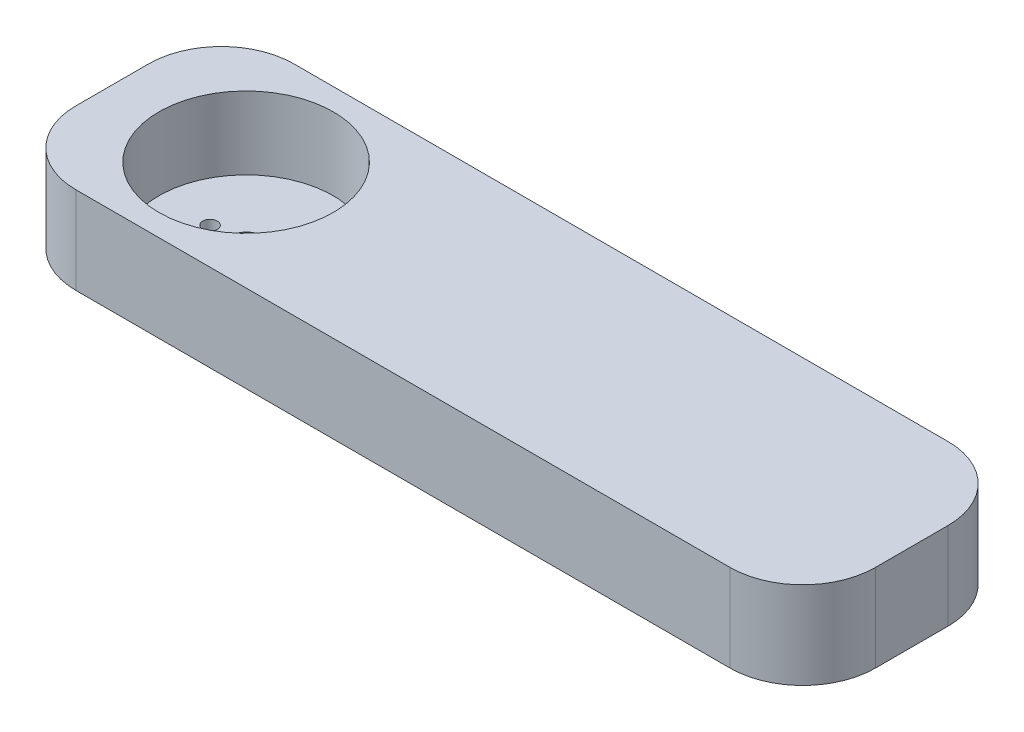
SolidWorks part; units mm, degrees
ref_plane "Front Plane" through (0, 0, 0) normal (0, 0, 1) x (1, 0, 0)
ref_plane "Top Plane" through (0, 0, 0) normal (0, 1, 0) x (1, 0, 0)
ref_plane "Right Plane" through (0, 0, 0) normal (1, 0, 0) x (0, 0, -1)
sketch "Sketch1" plane through (0, 0, 0) normal (0, 1, 0) x (1, 0, 0)
  line L1 (-49.6146, 18.5384) -> (60.3854, 18.5384)
  line L2 (-49.6146, 18.5384) -> (-49.6146, -11.4616)
  line L3 (-49.6146, -11.4616) -> (60.3854, -11.4616)
  line L4 (60.3854, 18.5384) -> (60.3854, -11.4616)
  dimension "D1" = 110
  dimension "D2" = 30
extrude "Boss-Extrude1" add sketch "Sketch1" along normal blind 12
fillet "Fillet1" radius 10 2 edges at (-49.6146, 6, -18.5384) (-49.6146, 6, 11.4616)
fillet "Fillet2" radius 10 2 edges at (60.3854, 6, -18.5384) (60.3854, 6, 11.4616)
sketch "Sketch9" plane through (0, 12, 0) normal (0, 1, 0) x (1, 0, 0)
  line L0 (-39.6146, -11.4616) -> (50.3854, -11.4616) construction
  circle A0 centre (-31.1958, 3.5384) radius 12
  dimension "D1" = 15
extrude "Cut-Extrude5" cut sketch "Sketch9" against normal blind 10
sketch "Sketch10" plane through (0, 2, 0) normal (0, 1, 0) x (1, 0, 0)
  circle A0 centre (-31.1477, 3.5384) radius 2.4
  circle A1 centre (-26.1318, 3.5384) radius 1
  circle A2 centre (-36.1636, 3.5384) radius 1
  circle A4 centre (-31.1958, 3.5384) radius 12 construction
  point P8 (0, 0)
  dimension "D1" = 12
extrude "Cut-Extrude6" cut sketch "Sketch10" against normal through all
